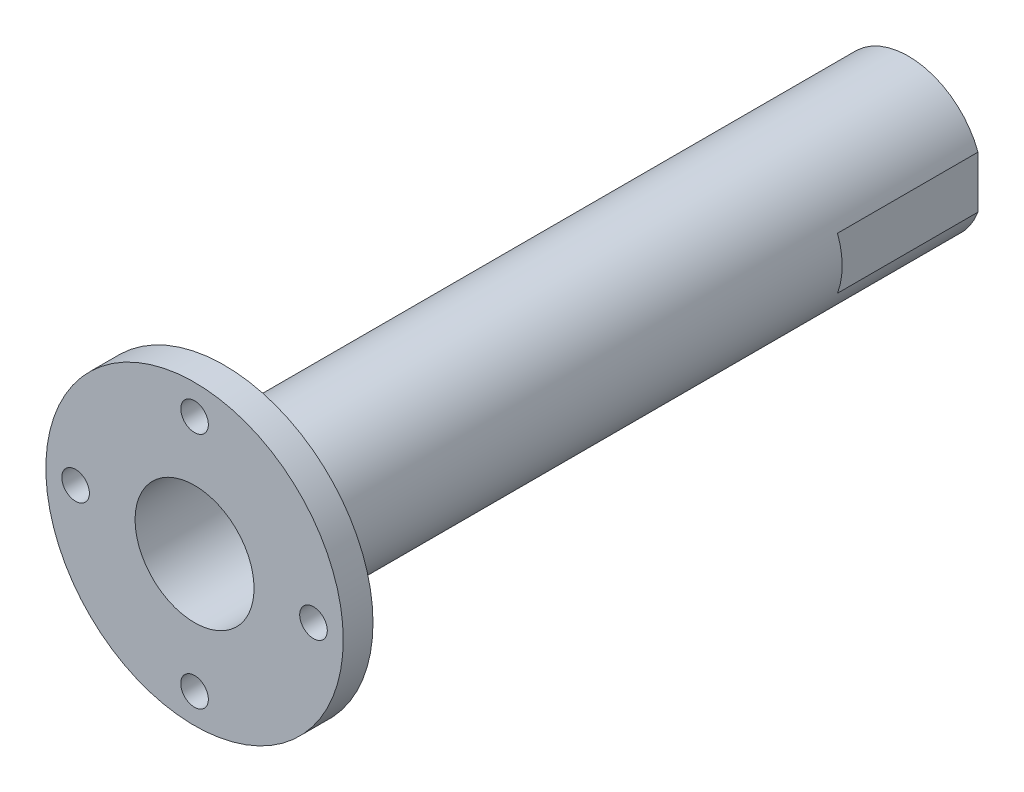
SolidWorks part; units mm, degrees
material "Tin Bearing Bronze"
ref_plane "Front Plane" through (0, 0, 0) normal (0, 0, 1) x (1, 0, 0)
ref_plane "Top Plane" through (0, 0, 0) normal (0, 1, 0) x (1, 0, 0)
ref_plane "Right Plane" through (0, 0, 0) normal (1, 0, 0) x (0, 0, -1)
sketch "Sketch1" plane through (0, 0, 0) normal (0, 0, 1) x (1, 0, 0)
  circle A0 centre (0, 0) radius 6.35
  circle A1 centre (0, 0) radius 7.9375
  dimension "D1" = 15.875
  dimension "D2" = 12.7
extrude "Boss-Extrude1" add sketch "Sketch1" along normal blind 76.2
sketch "Sketch2" plane through (0, 0, 76.2) normal (0, 0, 1) x (1, 0, 0)
  circle A0 centre (0, 0) radius 15.875
  circle A1 centre (0, 0) radius 6.35 construction
  circle A2 centre (0, 0) radius 6.35
  dimension "D1" = 31.75
extrude "Boss-Extrude2" add sketch "Sketch2" against normal blind 3.175
hole_wizard "#4 Clearance Hole1" positions "Sketch4" profile "Sketch5" hole size "#4" standard "ANSI Inch"
sketch "Sketch4" plane through (0, 0, 76.2) normal (0, 0, 1) x (1, 0, 0)
  point P0 (0, 12.7)
  point P2 (0, -12.7)
  point P4 (12.7, 0)
  point P6 (-12.7, 0)
  dimension "D1" = 12.7
  dimension "D2" = 12.7
  dimension "D3" = 12.7
  dimension "D4" = 12.7
sketch "Sketch5" plane through (0, 12.7, 76.2) normal (1, 0, 0) x (0, -1, 0)
  line L0 (0, 0) -> (0, 4.8852)
  line L1 (0, 4.8852) -> (1.4732, 4)
  line L2 (1.4732, 4) -> (1.4732, 0)
  line L5 (1.4732, 0) -> (0, 0)
  line L10 (0, 4.8852) -> (-1.4732, 4) construction
  line L11 (0, -6.35) -> (0, 107.95) construction
  dimension "Hole Dia." = 2.9464
  dimension "Hole Depth" = 4
  dimension "Drill Angle" = 118
sketch "Sketch6" plane through (0, 0, 0) normal (0, 1, 0) x (1, 0, 0)
  line L1 (7.4375, -15) -> (11.5746, -15)
  line L2 (7.4375, -73.025) -> (7.4375, 0)
  line L3 (7.4375, -73.025) -> (7.4375, 0)
  line L4 (7.4375, 0) -> (11.5746, 0)
  line L5 (11.5746, 0) -> (11.5746, -15)
  point P4 (9.5061, 0)
  dimension "D2" = 15
  dimension "D1" = 0.5
extrude "Cut-Extrude1" cut sketch "Sketch6" along normal through all both and the other way through all contours L5 L4 L3 L1
